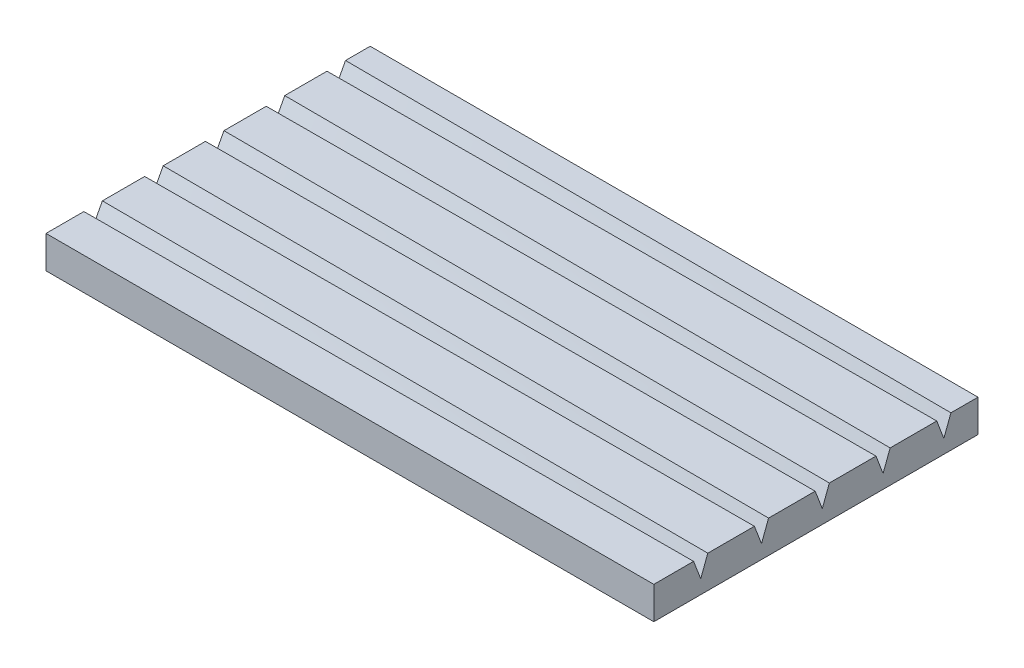
SolidWorks part; units mm, degrees
ref_plane "前视基准面" through (0, 0, 0) normal (0, 0, 1) x (1, 0, 0)
ref_plane "上视基准面" through (0, 0, 0) normal (0, 1, 0) x (1, 0, 0)
ref_plane "右视基准面" through (0, 0, 0) normal (1, 0, 0) x (0, 0, -1)
other "Configuration Table"
sketch "草图1" plane through (0, 0, 0) normal (0, 1, 0) x (1, 0, 0)
  line L1 (-75.2351, 39.9778) -> (74.7649, 39.9778)
  line L2 (-75.2351, 39.9778) -> (-75.2351, -40.0222)
  line L3 (-75.2351, -40.0222) -> (74.7649, -40.0222)
  line L4 (74.7649, 39.9778) -> (74.7649, -40.0222)
  dimension "D1" = 150
  dimension "D2" = 80
extrude "凸台-拉伸1" add sketch "草图1" along normal blind 8
ref_plane "基准面3" through (-75.2351, 0, 0) normal (-1, 0, 0) x (0, 0, 1)
sketch "草图7" plane through (-75.2351, 0, 0) normal (-1, 0, 0) x (0, 0, 1)
  line L0 (-44.1183, 8.4299) -> (-34.1183, 8.4299) construction
  line L1 (-34.1183, 8.4299) -> (-29.1183, 8.4299)
  line L2 (-29.1183, 8.4299) -> (-31.4715, 3.4299)
  line L3 (-31.4715, 3.4299) -> (-34.1183, 8.4299)
  dimension "D1" = 10
  dimension "D2" = 5
  dimension "D3" = 5
ref_plane "基准面5" through (-45.2351, 0, 0) normal (-1, 0, 0) x (0, 0, 1)
sketch "草图11" plane through (-45.2351, 0, 0) normal (-1, 0, 0) x (0, 0, 1)
  line L0 (-44.1183, 8.4299) -> (-33.7183, 8.4299) construction
  line L1 (-34.1183, 8.4299) -> (-29.1183, 8.4299) construction
  line L2 (-33.7183, 8.4299) -> (-29.5183, 8.4299)
  line L3 (-29.5183, 8.4299) -> (-31.6049, 3.4299)
  line L4 (-31.6049, 3.4299) -> (-33.7183, 8.4299)
  dimension "D1" = 10.4
  dimension "D2" = 4.2
  dimension "D3" = 5
ref_plane "基准面6" through (74.7649, 0, 0) normal (-1, 0, 0) x (0, 0, 1)
sketch "草图15" plane through (74.7649, 0, 0) normal (-1, 0, 0) x (0, 0, 1)
  line L0 (-44.0479, 8.4018) -> (-33.4479, 8.4018) construction
  line L1 (-33.4479, 8.4018) -> (-29.6479, 8.4018)
  line L2 (-29.6479, 8.4018) -> (-31.5479, 3.4018)
  line L3 (-31.5479, 3.4018) -> (-33.4479, 8.4018)
  dimension "D1" = 10.6
  dimension "D2" = 5
  dimension "3.8mm" = 3.8
loft "切除-放样1" cut profiles "草图7", "草图15"
pattern_linear "阵列(线性)1" count 5 spacing 15 along (0, 0, 1) of "切除-放样1"
